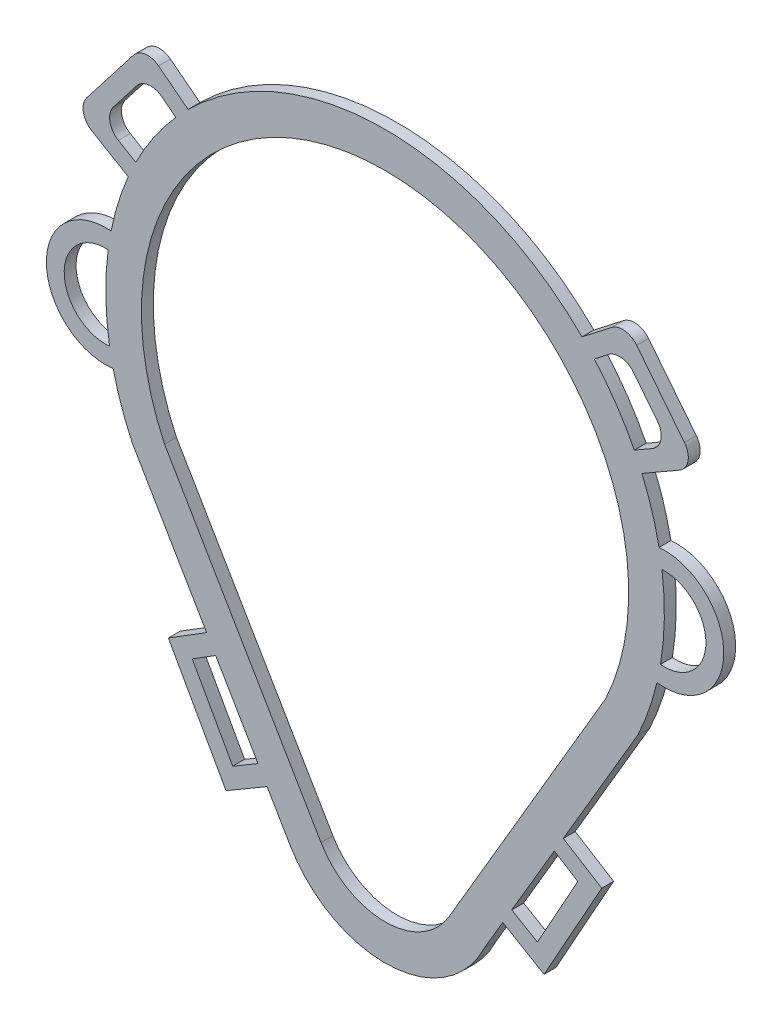
SolidWorks part; units mm, degrees
ref_plane "Front Plane" through (0, 0, 0) normal (0, 0, 1) x (1, 0, 0)
ref_plane "Top Plane" through (0, 0, 0) normal (0, 1, 0) x (1, 0, 0)
ref_plane "Right Plane" through (0, 0, 0) normal (1, 0, 0) x (0, 0, -1)
sketch "Sketch1" plane through (0, 0, 0) normal (0, 0, 1) x (1, 0, 0)
  line L0 (0, 41) -> (0, -67) construction
  line L5 (0, 0) -> (0, -56) construction
  line L6 (37.1057, -17.4403) -> (11.3127, -72.3172) construction
  line L7 (42.5358, -19.9925) -> (16.7428, -74.8694) construction
  line L8 (-37.1057, -17.4403) -> (-11.3127, -72.3172) construction
  line L9 (-42.5358, -19.9925) -> (-16.7428, -74.8694) construction
  line L10 (-37.1057, -17.4403) -> (-10.7824, -62.3237)
  line L11 (-42.5358, -19.9925) -> (-15.9623, -65.3515)
  line L12 (37.1057, -17.4403) -> (10.7824, -62.3237)
  line L13 (42.5358, -19.9925) -> (16.7077, -63.9433)
  arc A0 (37.1057, -17.4403) -> (-37.1057, -17.4403) centre (0, 0) ccw
  arc A2 (42.5358, -19.9925) -> (-42.5358, -19.9925) centre (0, 0) ccw
  arc A4 (-10.7824, -62.3237) -> (10.7824, -62.3237) centre (0, -56) ccw
  arc A5 (-16.7428, -74.8694) -> (16.7428, -74.8694) centre (0, -67) ccw construction
  arc A6 (-11.3127, -72.3172) -> (11.3127, -72.3172) centre (0, -67) ccw construction
  arc A7 (-15.9623, -65.3515) -> (16.7077, -63.9433) centre (0, -56) ccw
  dimension "D1" = 6
  dimension "D2" = 41
  dimension "D4" = 67
  dimension "D5" = 56
extrude "Boss-Extrude1" add sketch "Sketch1" along normal blind 2
sketch "Sketch2" plane through (0, 0, 2) normal (0, 0, 1) x (1, 0, 0)
  line L4 (0, 49.5385) -> (0, -93.5909) construction
  line L18 (28.473, -43.9228) -> (21.3216, -56.0921)
  line L19 (16.7077, -63.9433) -> (42.5358, -19.9925) construction
  line L20 (21.3216, -56.0921) -> (25.6324, -58.6253)
  line L21 (25.6324, -58.6253) -> (32.4455, -46.395)
  line L22 (32.4455, -46.395) -> (28.473, -43.9228)
  line L23 (26.7592, -62.7672) -> (36.4573, -45.3581)
  line L24 (36.4573, -45.3581) -> (27.4455, -39.75)
  line L25 (27.4455, -39.75) -> (17.2152, -57.1586)
  line L26 (17.2152, -57.1586) -> (26.7592, -62.7672)
  line L27 (-17.2152, -57.1586) -> (-26.7592, -62.7672)
  line L28 (-27.4455, -39.75) -> (-17.2152, -57.1586)
  line L29 (-36.4573, -45.3581) -> (-27.4455, -39.75)
  line L30 (-26.7592, -62.7672) -> (-36.4573, -45.3581)
  line L31 (-32.4455, -46.395) -> (-28.473, -43.9228)
  line L32 (-25.6324, -58.6253) -> (-32.4455, -46.395)
  line L33 (-21.3216, -56.0921) -> (-25.6324, -58.6253)
  line L34 (-28.473, -43.9228) -> (-21.3216, -56.0921)
  dimension "D1" = 3
  dimension "D4" = 14
  dimension "D5" = 5
extrude "Boss-Extrude2" add sketch "Sketch2" against normal blind 2
sketch "Sketch3" plane through (0, 0, 2) normal (0, 0, 1) x (1, 0, 0)
  line L0 (-35.214, 31.1284) -> (-37.5839, 32.9678)
  line L1 (-41.9377, 21.2186) -> (-44.876, 22.9491)
  line L2 (-41.7933, 32.4372) -> (-45.7234, 27.3735)
  line L3 (-35.214, 31.1284) -> (-41.9377, 21.2186)
  line L4 (-31.1514, 31.7728) -> (-38.1145, 37.1771)
  line L5 (-42.3238, 36.6466) -> (-50.1841, 26.519)
  line L6 (-41.0353, 17.2054) -> (-49.3367, 22.0947)
  line L7 (-31.1514, 31.7728) -> (-41.0353, 17.2054)
  line L8 (0, 0) -> (0, 76.5871) construction
  line L9 (31.1514, 31.7728) -> (41.0353, 17.2054)
  line L10 (41.0353, 17.2054) -> (49.5212, 22.0823)
  line L11 (42.3292, 36.6913) -> (50.3766, 26.5479)
  line L12 (31.1514, 31.7728) -> (38.1396, 37.1966)
  line L13 (35.214, 31.1284) -> (41.9377, 21.2186)
  line L14 (41.7986, 32.4819) -> (45.8142, 27.4204)
  line L15 (41.9377, 21.2186) -> (44.9589, 22.9548)
  line L16 (35.214, 31.1284) -> (37.6091, 32.9873)
  line L17 (-35.214, 31.1284) -> (-39.9539, 34.8072) construction
  line L18 (-39.9539, 34.8072) -> (-47.8142, 24.6797) construction
  line L19 (-31.1514, 31.7728) -> (-40.4844, 39.0165) construction
  line L20 (-40.4844, 39.0165) -> (-52.2749, 23.8252) construction
  line L21 (-41.0353, 17.2054) -> (-52.2749, 23.8252) construction
  line L22 (-41.9377, 21.2186) -> (-47.8142, 24.6797) construction
  circle A1 centre (-38.8928, 26.3885) radius 6 construction
  arc A2 (42.5358, -19.9925) -> (-42.5358, -19.9925) centre (0, 0) ccw construction
  circle A3 centre (38.8928, 26.3885) radius 6 construction
  arc A4 (-37.5839, 32.9678) -> (-41.7933, 32.4372) centre (-39.4233, 30.5978) ccw
  arc A5 (-38.1145, 37.1771) -> (-42.3238, 36.6466) centre (-39.9539, 34.8072) ccw
  arc A6 (-49.3367, 22.0947) -> (-50.1841, 26.519) centre (-47.8142, 24.6797) cw
  arc A7 (-44.876, 22.9491) -> (-45.7234, 27.3735) centre (-43.3535, 25.5341) cw
  arc A8 (44.9589, 22.9548) -> (45.8142, 27.4204) centre (43.464, 25.5559) ccw
  arc A9 (49.5212, 22.0823) -> (50.3766, 26.5479) centre (48.0264, 24.6833) ccw
  arc A10 (42.3292, 36.6913) -> (38.1396, 37.1966) centre (39.979, 34.8267) ccw
  arc A11 (37.6091, 32.9873) -> (41.7986, 32.4819) centre (39.4484, 30.6173) cw
  point P29 (-39.9539, 34.8072)
  point P33 (-40.4844, 39.0165)
  point P46 (40.4844, 39.0165)
  point P49 (39.9539, 34.8072)
  dimension "D1" = 3
  dimension "D2" = 12
  dimension "D3" = 3
  dimension "D4" = 3
extrude "Boss-Extrude3" add sketch "Sketch3" against normal blind 2
sketch "Sketch4" plane through (0, 0, 2) normal (0, 0, 1) x (1, 0, 0)
  line L0 (45.8484, 6.0673) -> (45.8484, -7.7445)
  line L1 (42.8484, 8.2623) -> (42.8484, -9.9395)
  line L2 (0, 0) -> (0, 26.9586) construction
  line L3 (-42.8484, 8.2623) -> (-42.8484, -9.9395)
  line L4 (-45.8484, 6.0673) -> (-45.8484, -7.7445)
  arc A0 (42.5358, -19.9925) -> (43.2221, 18.4621) centre (0, 0) ccw construction
  arc A1 (45.8484, -7.7445) -> (45.8484, 6.0673) centre (46.9925, -0.8386) ccw
  arc A2 (42.8484, -9.9395) -> (42.8484, 8.2623) centre (46.9925, -0.8386) ccw
  arc A3 (-42.8484, -9.9395) -> (-42.8484, 8.2623) centre (-46.9925, -0.8386) cw
  arc A4 (-45.8484, -7.7445) -> (-45.8484, 6.0673) centre (-46.9925, -0.8386) cw
  dimension "D1" = 3
extrude "Boss-Extrude4" add sketch "Sketch4" against normal blind 2
